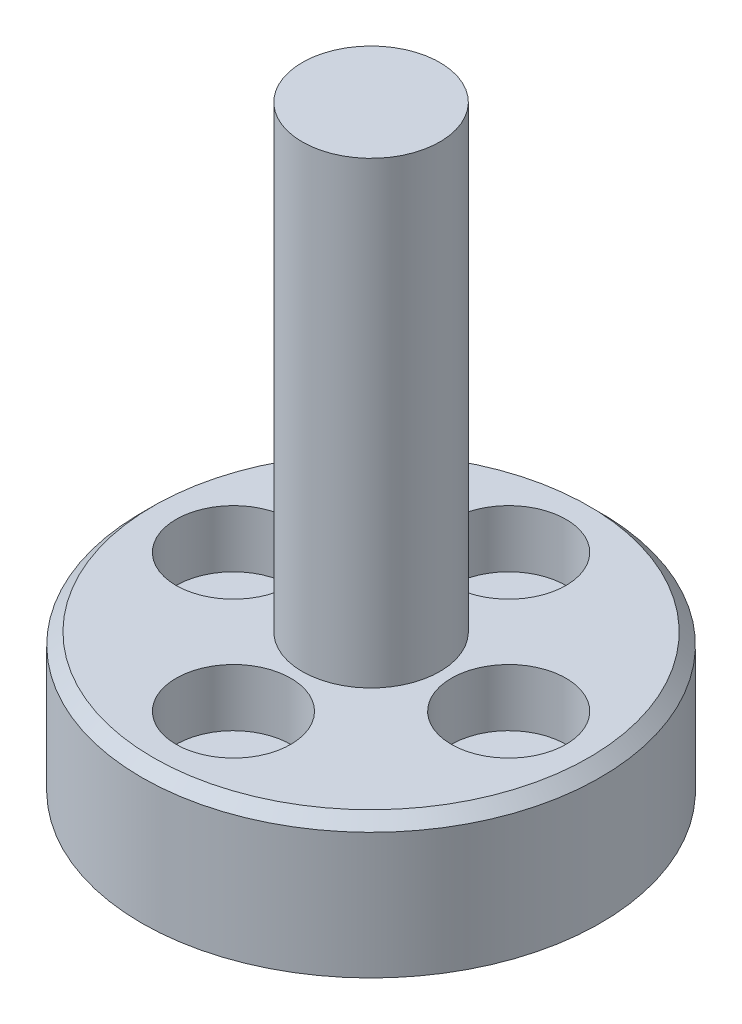
SolidWorks part; units mm, degrees
ref_plane "前视基准面" through (0, 0, 0) normal (0, 0, 1) x (1, 0, 0)
ref_plane "上视基准面" through (0, 0, 0) normal (0, 1, 0) x (1, 0, 0)
ref_plane "右视基准面" through (0, 0, 0) normal (1, 0, 0) x (0, 0, -1)
other "Configuration Table"
sketch "草图1" plane through (0, 0, 0) normal (0, 0, 1) x (1, 0, 0)
  line L0 (0, 9.9473) -> (0, -12.0981) construction
  line L1 (0, 26) -> (3, 26)
  line L2 (3, 26) -> (3, 6)
  line L3 (3, 6) -> (9.5, 6)
  line L4 (10, 5.5) -> (10, 0)
  line L5 (10, 0) -> (3, 0)
  line L6 (3, 0) -> (3, 3)
  line L7 (3, 3) -> (0, 3)
  line L8 (9.5, 6) -> (10, 5.5)
  line L9 (0, 26) -> (0, 3)
  line L10 (6, 7.6882) -> (6, -3.7802) construction
  point P7 (10, 6)
  dimension "D1" = 6
  dimension "D2" = 6
  dimension "D3" = 10
  dimension "D4" = 20
  dimension "D5" = 3
  dimension "D6" = 3
  dimension "D7" = 6
revolve "旋转1" add sketch "草图1" angle 360 about L0
sketch "草图2" plane through (0, 6, 0) normal (0, 1, 0) x (1, 0, 0)
  circle A0 centre (0, 6) radius 1
  circle A1 centre (6, 0) radius 1
  circle A2 centre (0, -6) radius 1
  circle A3 centre (-6, 0) radius 1
  point P12 (0, 0)
  dimension "D1" = 6
  dimension "D2" = 2
  dimension "D3" = 4
extrude "切除-拉伸1" cut sketch "草图2" against normal blind 10
sketch "草图3" plane through (0, 6, 0) normal (0, 1, 0) x (1, 0, 0)
  circle A0 centre (0, 6) radius 2.5
  circle A1 centre (6, 0) radius 2.5
  circle A2 centre (0, -6) radius 2.5
  circle A3 centre (-6, 0) radius 2.5
  point P12 (0, 0)
  dimension "D1" = 5
  dimension "D2" = 4
extrude "切除-拉伸2" cut sketch "草图3" against normal blind 2.5
